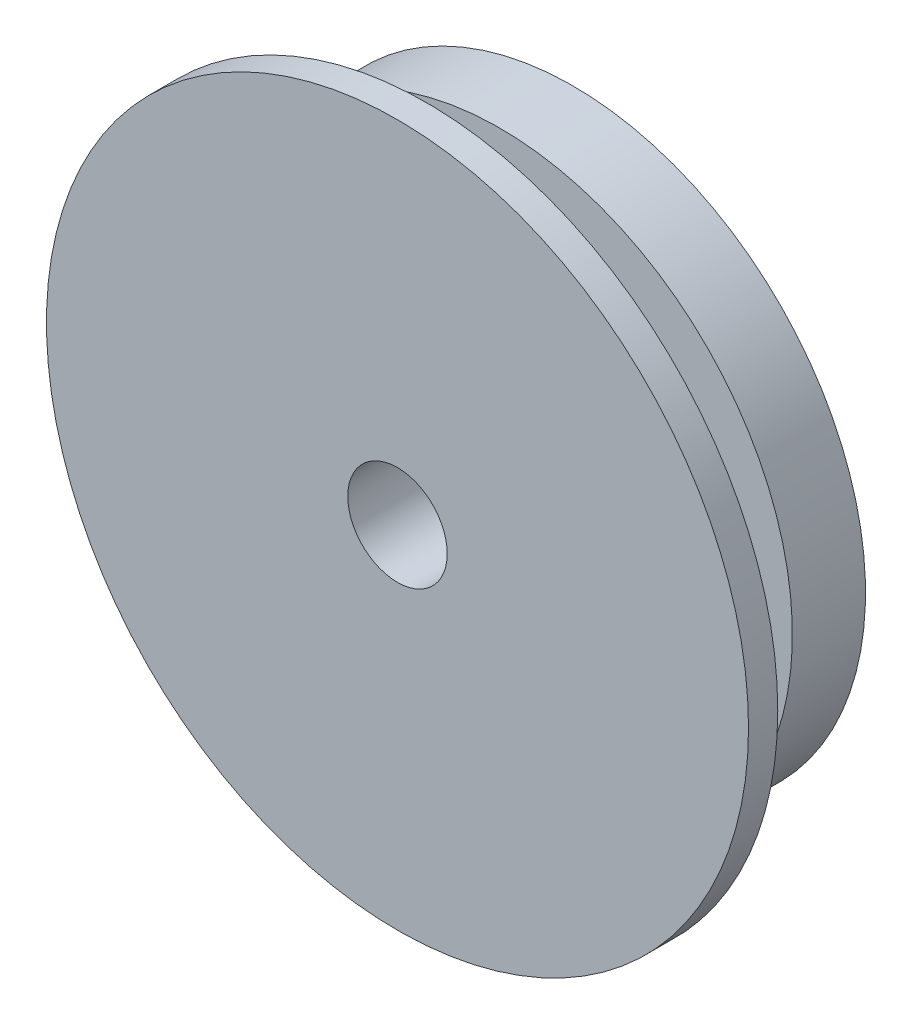
SolidWorks part; units mm, degrees
material "Resina de melamina"
ref_plane "Alzado" through (0, 0, 0) normal (0, 0, 1) x (1, 0, 0)
ref_plane "Planta" through (0, 0, 0) normal (0, 1, 0) x (1, 0, 0)
ref_plane "Vista lateral" through (0, 0, 0) normal (1, 0, 0) x (0, 0, -1)
sketch "Croquis1" plane through (0, 0, 0) normal (0, 0, 1) x (1, 0, 0)
  circle A0 centre (0, 0) radius 11
  circle A1 centre (0, 0) radius 25
  dimension "D1" = 50
  dimension "D2" = 22
extrude "Saliente-Extruir1" add sketch "Croquis1" along normal blind 16.5
ref_plane "Plano1" through (0, 0, 6) normal (0, 0, -1) x (-1, 0, 0)
sketch "Croquis3" plane through (0, 0, 6) normal (0, 0, -1) x (-1, 0, 0)
  circle A0 centre (0, 0) radius 11
  circle A1 centre (0, 0) radius 9.5
  dimension "D1" = 19
extrude "Saliente-Extruir2" add sketch "Croquis3" against normal through all
sketch "Croquis4" plane through (0, 0, 16.5) normal (0, 0, 1) x (1, 0, 0)
  circle A0 centre (0, 0) radius 11
  circle A1 centre (0, 0) radius 4
  dimension "D1" = 8
extrude "Saliente-Extruir3" add sketch "Croquis4" against normal blind 2
sketch "Croquis5" plane through (0, 0, 16.5) normal (0, 0, 1) x (1, 0, 0)
  circle A0 centre (0, 0) radius 25
  circle A1 centre (0, 0) radius 30
  dimension "D1" = 60
extrude "Saliente-Extruir4" add sketch "Croquis5" against normal blind 2.5
ref_plane "Plano2" through (0, 0, 11.75) normal (0, 0, -1) x (-1, 0, 0)
sketch "Croquis6" plane through (0, 0, 11.75) normal (0, 0, -1) x (-1, 0, 0)
  circle A1 centre (0, 0) radius 25
  circle A2 centre (0, 0) radius 19
  dimension "D1" = 38
extrude "Cortar-Extruir1" cut sketch "Croquis6" along normal blind 4
sketch "Croquis7" plane through (0, 0, 0) normal (0, 0, -1) x (-1, 0, 0)
  circle A0 centre (0, 0) radius 11
  circle A1 centre (0, 0) radius 4.25
  dimension "D1" = 8.5
extrude "Saliente-Extruir5" add sketch "Croquis7" against normal through all
sketch "Croquis8" plane through (0, 0, 0) normal (0, 0, -1) x (-1, 0, 0)
  circle A0 centre (0, 0) radius 6.1
  circle A1 centre (0, 0) radius 4
  dimension "D1" = 12.2
extrude "Saliente-Extruir6" add sketch "Croquis8" along normal blind 2
sketch "Croquis11" plane through (0, 0, 0) normal (0, 0, -1) x (-1, 0, 0)
  circle A0 centre (0, 0) radius 15
  circle A1 centre (0, 0) radius 25
  dimension "D1" = 30
extrude "Cortar-Extruir2" cut sketch "Croquis11" against normal blind 1.5
sketch "Croquis13" plane through (0, 0, 14.5) normal (0, 0, -1) x (-1, 0, 0)
  circle A0 centre (0, 0) radius 4.25
extrude "Cortar-Extruir5" cut sketch "Croquis13" against normal blind 10
sketch "Croquis14" plane through (0, 0, 0) normal (0, 0, 1) x (1, 0, 0)
  circle A0 centre (0, 0) radius 4.25
extrude "Cortar-Extruir6" cut sketch "Croquis14" against normal blind 10
